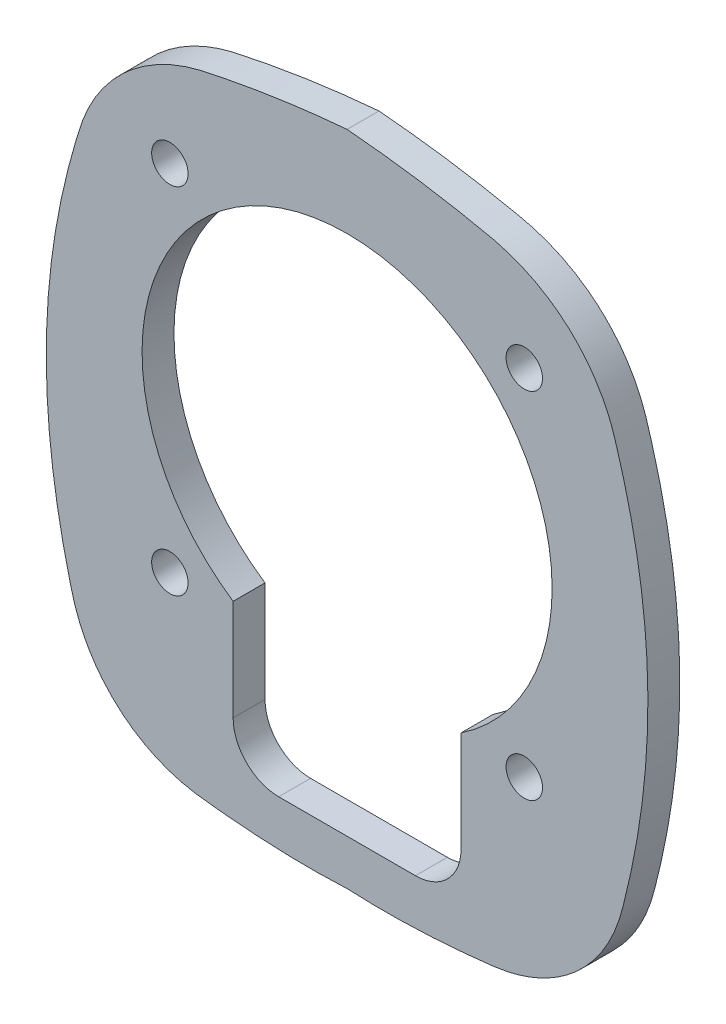
SolidWorks part; units mm, degrees
material "Фанера"
ref_plane "Front Plane" through (0, 0, 0) normal (0, 0, 1) x (1, 0, 0)
ref_plane "Top Plane" through (0, 0, 0) normal (0, 1, 0) x (1, 0, 0)
ref_plane "Right Plane" through (0, 0, 0) normal (1, 0, 0) x (0, 0, -1)
sketch "Эскиз1" plane through (0, 0, 0) normal (0, 0, 1) x (1, 0, 0)
  line L0 (-0.0015, 60.5557) -> (-0.0015, 134.2053) construction
  line L1 (-9.4848, 103.6369) -> (10.8304, 103.6369) construction
  line L6 (-6.0049, 75.812) -> (6.002, 75.812)
  line L7 (-0.0015, 85.6388) -> (0, 85.6369) construction
  line L8 (-0.0015, 85.6351) -> (0, 85.6369) construction
  line L9 (-10.0049, 79.812) -> (-10.0049, 88.6736)
  line L11 (10.002, 79.812) -> (10.002, 88.6716)
  line L12 (-10.0049, 75.812) -> (0.0004, 85.6369) construction
  line L13 (-0.0034, 85.6369) -> (10.002, 75.812) construction
  line L14 (-7.2738, 96.3631) -> (9.1571, 112.794) construction
  arc A0 (6.002, 75.812) -> (10.002, 79.812) centre (6.002, 79.812) ccw
  circle A1 centre (0, 103.6369) radius 4.3081 construction
  arc A2 (10.002, 88.6716) -> (-10.0049, 88.6736) centre (0, 103.6369) ccw
  arc A5 (-6.0049, 75.812) -> (-10.0049, 79.812) centre (-6.0049, 79.812) cw
  arc A6 (-0.0034, 85.6369) -> (0.0004, 85.6369) centre (0, 103.6369) ccw
  circle A7 centre (15.5563, 119.1933) radius 1.6
  circle A8 centre (-15.5593, 119.1933) radius 1.6
  circle A9 centre (15.5563, 88.0806) radius 1.6
  circle A10 centre (-15.5593, 88.0806) radius 1.6
  spline S2 degree 3 poles (0, 71.8315) (0.2244, 71.8205) (0.6841, 71.7981) (1.3906, 71.7739) (2.1299, 71.7565) (3.1203, 71.7448) (4.3408, 71.7502) (6.2668, 71.7976) (8.2168, 71.9045) (10.1384, 72.0606) (11.3175, 72.1756) (12.1908, 72.2722) (12.8055, 72.3427) (13.3777, 72.421) (13.9058, 72.5162) (14.7105, 72.6907) (15.8008, 73.0104) (17.1419, 73.5688) (18.4173, 74.2756) (19.9923, 75.3961) (21.3613, 76.7726) (22.4812, 78.3513) (23.0689, 79.4057) (23.4749, 80.2949) (23.7299, 80.9415) (23.9658, 81.6338) (24.1533, 82.3069) (24.3304, 83.0036) (24.4986, 83.6829) (24.6729, 84.4203) (24.8945, 85.4038) (25.1479, 86.6174) (25.5149, 88.5753) (25.8823, 90.9622) (26.3008, 94.8042) (26.4639, 98.6624) (26.342, 102.5416) (26.1061, 105.4752) (25.7399, 108.3214) (25.2271, 111.2025) (24.5892, 114.0183) (24.0127, 116.1281) (23.5945, 117.5099) (23.393, 118.1622) (23.1446, 118.8493) (22.5789, 120.197) (21.3958, 122.2037) (19.3962, 124.3599) (17.5808, 125.6554) (16.3202, 126.3458) (15.5998, 126.6908) (14.887, 126.9875) (14.1857, 127.2392) (13.4993, 127.4491) (12.8305, 127.6212) (12.1801, 127.7583) (11.2759, 127.9477) (10.1086, 128.1784) (8.6711, 128.4415) (7.236, 128.6816) (5.7947, 128.9003) (4.3525, 129.0967) (2.9098, 129.2708) (1.4615, 129.4257) (0.4914, 129.5118) (0, 129.5554) knots 0 0 0 0 0.007245 0.014841 0.02279 0.031091 0.046775 0.062143 0.093208 0.109725 0.124306 0.131407 0.138054 0.144258 0.150025 0.155351 0.170805 0.186581 0.2021 0.217718 0.248803 0.264075 0.280043 0.287632 0.295585 0.302443 0.311207 0.318104 0.325624 0.333769 0.342538 0.358129 0.373741 0.406766 0.435965 0.498333 0.531062 0.561065 0.593194 0.623552 0.655389 0.686255 0.694049 0.701943 0.708265 0.717598 0.749054 0.782774 0.811662 0.820523 0.829105 0.837402 0.845408 0.85312 0.860537 0.867667 0.874549 0.890325 0.906032 0.92167 0.937239 0.953036 0.968597 0.984095 1 1 1 1
  spline S3 degree 3 poles (0, 129.5554) (-0.3274, 129.5268) (-0.9768, 129.4701) (-1.9414, 129.3741) (-3.0563, 129.2533) (-4.3335, 129.0991) (-5.9304, 128.8821) (-7.6867, 128.6115) (-9.5968, 128.2774) (-11.1065, 127.983) (-12.2257, 127.749) (-12.9657, 127.5909) (-13.7283, 127.3844) (-14.5123, 127.1287) (-15.3133, 126.8172) (-16.1261, 126.4457) (-17.4441, 125.7433) (-19.2803, 124.4583) (-20.8975, 122.7541) (-22.0344, 121.1141) (-22.6475, 120.0027) (-23.0613, 119.0569) (-23.2906, 118.4513) (-23.4514, 117.9742) (-23.5936, 117.5109) (-23.9627, 116.299) (-24.5204, 114.2893) (-25.1661, 111.4983) (-25.6891, 108.6448) (-26.202, 104.8285) (-26.4995, 99.9805) (-26.3292, 95.2328) (-25.9381, 91.395) (-25.5882, 89.016) (-25.2309, 87.0441) (-24.9441, 85.6271) (-24.6298, 84.2176) (-24.3543, 83.096) (-24.1482, 82.29) (-24.0189, 81.8236) (-23.8541, 81.2982) (-23.6443, 80.7117) (-23.262, 79.7982) (-22.7055, 78.7194) (-21.6227, 77.0848) (-20.2754, 75.645) (-18.7079, 74.4633) (-17.4335, 73.7134) (-16.0912, 73.1162) (-14.7298, 72.6834) (-13.29, 72.3869) (-12.0158, 72.2517) (-10.861, 72.1299) (-9.8822, 72.0402) (-8.6902, 71.9441) (-7.3519, 71.8569) (-5.8859, 71.7894) (-4.4312, 71.7513) (-2.9337, 71.7436) (-1.4525, 71.766) (-0.4689, 71.8103) (0, 71.8315) knots 0 0 0 0 0.010598 0.021016 0.031255 0.046759 0.062493 0.083214 0.104054 0.125012 0.132806 0.140921 0.149406 0.158267 0.167501 0.177102 0.187061 0.215635 0.248952 0.262143 0.279925 0.289768 0.295408 0.3008 0.305999 0.311032 0.341649 0.373226 0.403368 0.435154 0.497342 0.559715 0.588091 0.621706 0.637214 0.652703 0.668319 0.683771 0.689942 0.695141 0.699374 0.707697 0.715212 0.731297 0.746741 0.778348 0.794222 0.80993 0.825917 0.841493 0.855899 0.873235 0.88278 0.893344 0.904924 0.92134 0.936583 0.952242 0.968255 0.984867 1 1 1 1
  spline S4 degree 1 poles (0.0005, 130.3585) (-0.0015, 71.0306) knots 0 0 1 1 construction
  spline S5 degree 1 poles (-0.0015, 71.0306) (0.0005, 130.3585) knots 0 0 1 1 construction
  spline S6 degree 3 poles (0.0005, 130.3585) (-1.9455, 130.1885) (-4.8584, 129.8688) (-8.7224, 129.2582) (-11.1223, 128.7926) (-13.0359, 128.4094) (-15.0232, 127.8493) (-17.3518, 126.8009) (-19.874, 125.0131) (-21.9837, 122.7455) (-23.3158, 120.5504) (-24.0971, 118.6337) (-24.6645, 116.74) (-25.3246, 114.3845) (-26.1998, 110.5525) (-26.9602, 105.6954) (-27.3032, 99.7997) (-27.1111, 94.8853) (-26.6923, 90.981) (-26.2473, 88.0692) (-25.7783, 85.667) (-25.339, 83.7483) (-24.996, 82.3391) (-24.576, 80.8596) (-23.7922, 78.961) (-22.4474, 76.7543) (-20.2746, 74.5173) (-17.6592, 72.8344) (-15.2321, 71.9467) (-13.2018, 71.569) (-11.2484, 71.3655) (-8.819, 71.135) (-5.8821, 70.9752) (-2.9406, 70.9249) (-0.9807, 70.9865) (-0.0015, 71.0306) knots -0.000757 -0.000757 -0.000757 -0.000757 0.061765 0.093026 0.124287 0.139918 0.155548 0.186809 0.21807 0.249331 0.280592 0.296223 0.311853 0.343114 0.374376 0.436898 0.49942 0.561942 0.593203 0.624464 0.655725 0.671356 0.686986 0.702617 0.718247 0.749508 0.780769 0.81203 0.843291 0.858922 0.874552 0.905813 0.937074 0.968336 0.999597 0.999597 0.999597 0.999597 construction
  spline S7 degree 3 poles (-0.0015, 71.0306) (1.9571, 70.9351) (4.9047, 70.92) (8.8167, 71.1355) (11.2546, 71.365) (13.1961, 71.5697) (15.2349, 71.9462) (17.6573, 72.8341) (20.2745, 74.5172) (22.4473, 76.7538) (23.7915, 78.96) (24.5757, 80.8579) (24.9949, 82.336) (25.3393, 83.7482) (25.7774, 85.6645) (26.2473, 88.0682) (26.6919, 90.9795) (27.1112, 94.8837) (27.3031, 99.7988) (26.9607, 105.6913) (26.2004, 110.549) (25.3257, 114.3811) (24.6652, 116.7361) (24.0982, 118.6308) (23.3179, 120.5463) (21.9828, 122.7473) (19.8733, 125.0135) (17.3516, 126.8011) (15.0221, 127.8495) (13.0373, 128.4093) (11.1214, 128.7928) (8.7226, 129.2581) (4.8581, 129.8693) (1.946, 130.1859) (0.0005, 130.3585) knots 0.000403 0.000403 0.000403 0.000403 0.062925 0.094187 0.125448 0.141078 0.156709 0.18797 0.219231 0.250492 0.281753 0.297383 0.313014 0.328644 0.344275 0.375536 0.406797 0.438058 0.50058 0.563102 0.625624 0.656886 0.688147 0.703777 0.719408 0.750669 0.78193 0.813191 0.844452 0.860082 0.875713 0.906974 0.938235 1.000757 1.000757 1.000757 1.000757 construction
  point P9 (0, 85.6369)
  dimension "D2" = 36
  dimension "D3" = 4
  dimension "D5" = 3.2
  dimension "D4" = 45
  dimension "D6" = 22
  dimension "D1" = 0.8
extrude "Бобышка-Вытянуть1" add sketch "Эскиз1" along normal mid plane 2.8 contours S6 S7 A9 L6 A5 L9 A2 L11 A0 A7 A8 A10
